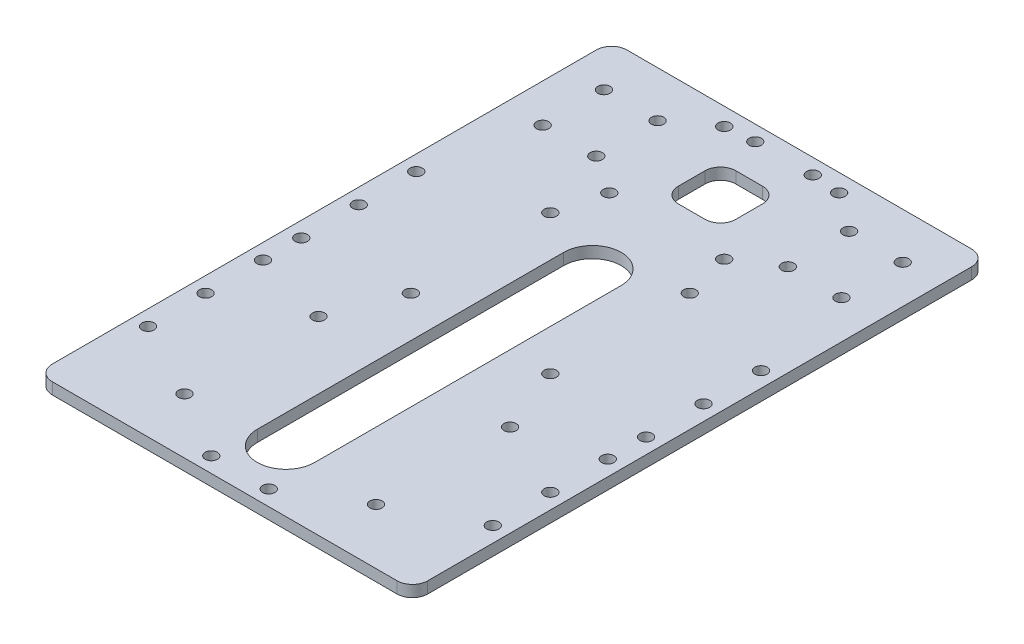
SolidWorks part; units mm, degrees
ref_plane "前视基准面" through (0, 0, 0) normal (0, 0, 1) x (1, 0, 0)
ref_plane "上视基准面" through (0, 0, 0) normal (0, 1, 0) x (1, 0, 0)
ref_plane "右视基准面" through (0, 0, 0) normal (1, 0, 0) x (0, 0, -1)
sketch "草图3" plane through (0, 0, 0) normal (0, 1, 0) x (1, 0, 0)
  line L1 (-49, -75) -> (49, -75)
  line L2 (-49, -75) -> (-49, 75)
  line L3 (-49, 75) -> (49, 75)
  line L4 (49, -75) -> (49, 75)
  line L5 (-49, -75) -> (49, 75) construction
  line L6 (-49, 75) -> (49, -75) construction
  point P0 (0, 0)
  dimension "D1" = 98
  dimension "D2" = 150
sketch "草图4" plane through (0, 0, 0) normal (0, 1, 0) x (1, 0, 0)
  line L1 (-75, -125) -> (75, -125)
  line L2 (-75, -125) -> (-75, 125)
  line L3 (-75, 125) -> (75, 125)
  line L4 (75, -125) -> (75, 125)
  line L5 (-75, -125) -> (75, 125) construction
  line L6 (-75, 125) -> (75, -125) construction
  point P0 (0, 0)
  dimension "D1" = 150
  dimension "D2" = 250
extrude "凸台-拉伸1" add sketch "草图3" along normal blind 3
fillet "圆角1" radius 4 4 edges at (-49, 1.5, -75) (49, 1.5, -75) (-49, 1.5, 75) (49, 1.5, 75)
sketch "草图5" plane through (0, 0, 0) normal (0, -1, 0) x (1, 0, 0)
  line L0 (0, -75) -> (0, 8.4939) construction
  line L1 (45, -75) -> (-45, -75) construction
  line L2 (-49, -55) -> (49, -55) construction
  line L3 (-49, -71) -> (-49, 71) construction
  line L4 (49, 71) -> (49, -71) construction
  line L5 (-32, -47) -> (-32, -63) construction
  line L6 (-39, -63) -> (-25, -63) construction
  line L7 (-39, -63) -> (-39, -47) construction
  line L8 (-39, -47) -> (-25, -47) construction
  line L9 (-25, -63) -> (-25, -47) construction
  line L10 (-39, -63) -> (-25, -47) construction
  line L11 (-39, -47) -> (-25, -63) construction
  circle A0 centre (-39, -47) radius 1.6
  circle A1 centre (-25, -47) radius 1.6
  circle A2 centre (-39, -63) radius 1.6
  circle A3 centre (-25, -63) radius 1.6
  circle A4 centre (25, -47) radius 1.6
  circle A5 centre (25, -63) radius 1.6
  circle A6 centre (39, -63) radius 1.6
  circle A7 centre (39, -47) radius 1.6
  point P11 (-32, -55)
  dimension "D3" = 3.2
  dimension "D1" = 14
  dimension "D2" = 16
  dimension "D4" = 20
  dimension "D5" = 17
extrude "切除-拉伸1" cut sketch "草图5" against normal blind 3
sketch "草图6" plane through (0, 0, 0) normal (0, -1, 0) x (1, 0, 0)
  line L0 (0, 75) -> (0, -75) construction
  line L1 (-45, 75) -> (45, 75) construction
  line L2 (45, -75) -> (-45, -75) construction
  line L3 (-49, 43) -> (49, 43) construction
  line L4 (-49, -71) -> (-49, 71) construction
  line L5 (49, 71) -> (49, -71) construction
  line L6 (-25, 60.5) -> (-25, 25.5) construction
  line L7 (25, 60.5) -> (25, 25.5) construction
  circle A0 centre (-25, 60.5) radius 1.6
  circle A1 centre (-25, 25.5) radius 1.6
  circle A2 centre (25, 60.5) radius 1.6
  circle A3 centre (25, 25.5) radius 1.6
  dimension "D2" = 3.2
  dimension "D1" = 35
  dimension "D3" = 25
  dimension "D4" = 32
extrude "切除-拉伸2" cut sketch "草图6" against normal blind 3
sketch "草图7" plane through (0, 0, 0) normal (0, -1, 0) x (1, 0, 0)
  line L0 (0, -75) -> (0, 75) construction
  line L1 (45, -75) -> (-45, -75) construction
  line L2 (-45, 75) -> (45, 75) construction
  line L3 (-49, -10) -> (49, -10) construction
  line L4 (-49, -71) -> (-49, 71) construction
  line L5 (49, 71) -> (49, -71) construction
  line L7 (-18.2, -28.2) -> (18.2, -28.2) construction
  line L8 (-18.2, -28.2) -> (-18.2, 8.2) construction
  line L9 (-18.2, 8.2) -> (18.2, 8.2) construction
  line L10 (18.2, -28.2) -> (18.2, 8.2) construction
  line L11 (-18.2, -28.2) -> (18.2, 8.2) construction
  line L12 (-18.2, 8.2) -> (18.2, -28.2) construction
  circle A0 centre (-18.2, 8.2) radius 1.6
  circle A1 centre (18.2, 8.2) radius 1.6
  circle A2 centre (18.2, -28.2) radius 1.6
  circle A3 centre (-18.2, -28.2) radius 1.6
  point P12 (0, -10)
  dimension "D3" = 3.2
  dimension "D1" = 36.4
  dimension "D2" = 36.4
  dimension "D4" = 65
extrude "切除-拉伸3" cut sketch "草图7" against normal blind 3
sketch "草图8" plane through (0, 0, 0) normal (0, -1, 0) x (1, 0, 0)
  line L0 (0, -75) -> (0, 75) construction
  line L1 (45, -75) -> (-45, -75) construction
  line L2 (-45, 75) -> (45, 75) construction
  line L3 (-49, 15) -> (49, 15) construction
  line L4 (-49, -71) -> (-49, 71) construction
  line L5 (49, 71) -> (49, -71) construction
  line L7 (-45, -20) -> (45, -20) construction
  line L8 (-45, -20) -> (-45, 50) construction
  line L9 (-45, 50) -> (45, 50) construction
  line L10 (45, -20) -> (45, 50) construction
  line L11 (-45, -20) -> (45, 50) construction
  line L12 (-45, 50) -> (45, -20) construction
  circle A0 centre (45, 50) radius 1.6
  circle A1 centre (-45, 50) radius 1.6
  circle A2 centre (45, -20) radius 1.6
  circle A3 centre (-45, -20) radius 1.6
  point P12 (0, 15)
  dimension "D3" = 3.2
  dimension "D1" = 90
  dimension "D2" = 70
  dimension "D4" = 90
extrude "切除-拉伸4" cut sketch "草图8" against normal blind 3
sketch "草图9" plane through (0, 0, 0) normal (0, -1, 0) x (1, 0, 0)
  line L0 (0, 75) -> (0, -75) construction
  line L1 (-45, 75) -> (45, 75) construction
  line L2 (45, -75) -> (-45, -75) construction
  line L3 (-49, -71) -> (-49, 71) construction
  line L4 (-49, 35) -> (-45, 35) construction
  line L5 (-49, 35) -> (-49, 20) construction
  line L6 (-49, 20) -> (-45, 20) construction
  line L7 (-45, 35) -> (-45, 20) construction
  line L8 (-15.7692, 0) -> (14.4467, 0) construction
  line L9 (-49, 10) -> (-45, 10) construction
  line L10 (-49, 10) -> (-49, -5) construction
  line L11 (-49, -5) -> (-45, -5) construction
  line L12 (-45, 10) -> (-45, -5) construction
  line L13 (-7.5, 75) -> (7.5, 75) construction
  line L14 (-7.5, 75) -> (-7.5, 71) construction
  line L15 (-7.5, 71) -> (7.5, 71) construction
  line L16 (7.5, 75) -> (7.5, 71) construction
  circle A0 centre (-45, 35) radius 1.6
  circle A1 centre (-45, 20) radius 1.6
  circle A2 centre (45, 20) radius 1.6
  circle A3 centre (45, 35) radius 1.6
  circle A4 centre (-45, 10) radius 1.6
  circle A5 centre (-45, -5) radius 1.6
  circle A6 centre (45, 10) radius 1.6
  circle A7 centre (45, -5) radius 1.6
  circle A8 centre (-7.5, 71) radius 1.6
  circle A9 centre (7.5, 71) radius 1.6
  circle A10 centre (7.5, -71) radius 1.6
  circle A11 centre (-7.5, -71) radius 1.6
  dimension "D3" = 3.2
  dimension "D4" = 3.2
  dimension "D9" = 3.2
  dimension "D10" = 3.2
  dimension "D13" = 3.2
  dimension "D14" = 3.2
  dimension "D1" = 15
  dimension "D2" = 4
  dimension "D5" = 40
  dimension "D6" = 15
  dimension "D7" = 10
  dimension "D8" = 4
  dimension "D11" = 15
  dimension "D12" = 4
extrude "切除-拉伸5" cut sketch "草图9" against normal blind 10
sketch "草图10" plane through (0, 3, 0) normal (0, 1, 0) x (1, 0, 0)
  line L0 (0, 75) -> (0, 0) construction
  line L1 (45, 75) -> (-45, 75) construction
  line L2 (-15, 55.3949) -> (15, 55.3949) construction
  line L3 (-15, 70.3949) -> (15, 70.3949) construction
  line L4 (-15, 70.3949) -> (-15, 40.3949) construction
  line L5 (-15, 40.3949) -> (15, 40.3949) construction
  line L6 (15, 70.3949) -> (15, 40.3949) construction
  line L7 (-15, 70.3949) -> (15, 40.3949) construction
  line L8 (-15, 40.3949) -> (15, 70.3949) construction
  circle A0 centre (-15, 70.3949) radius 1.6
  circle A1 centre (15, 70.3949) radius 1.6
  circle A2 centre (-15, 40.3949) radius 1.6
  circle A3 centre (15, 40.3949) radius 1.6
  point P5 (0, 55.3949)
  dimension "D3" = 3.2
  dimension "D1" = 30
  dimension "D2" = 30
extrude "切除-拉伸6" cut sketch "草图10" against normal blind 10
sketch "草图11" plane through (0, 3, 0) normal (0, 1, 0) x (1, 0, 0)
  line L0 (0, -59) -> (0, 21) construction
  line L1 (-7.5, -59) -> (-7.5, 21)
  line L2 (7.5, -59) -> (7.5, 21)
  line L3 (-45, -75) -> (45, -75) construction
  line L4 (0, 21) -> (0, 75) construction
  line L5 (-7.5, 61.9104) -> (7.5, 61.9104)
  line L6 (-7.5, 61.9104) -> (-7.5, 46.9104)
  line L7 (-7.5, 46.9104) -> (7.5, 46.9104)
  line L8 (7.5, 61.9104) -> (7.5, 46.9104)
  line L9 (-7.5, 61.9104) -> (7.5, 46.9104) construction
  line L10 (-7.5, 46.9104) -> (7.5, 61.9104) construction
  line L11 (45, 75) -> (-45, 75) construction
  arc A0 (-7.5, -59) -> (7.5, -59) centre (0, -59) ccw
  arc A1 (7.5, 21) -> (-7.5, 21) centre (0, 21) ccw
  point P3 (0, -19)
  point P10 (0, 54.4104)
  point P19 (0, 0)
  dimension "D1" = 15
  dimension "D2" = 80
  dimension "D3" = 16
  dimension "D4" = 15
  dimension "D5" = 15
extrude "切除-拉伸7" cut sketch "草图11" against normal blind 10
fillet "圆角2" radius 4 4 edges at (-7.5, 1.5, -46.9104) (7.5, 1.5, -46.9104) (7.5, 1.5, -61.9104) (-7.5, 1.5, -61.9104)
